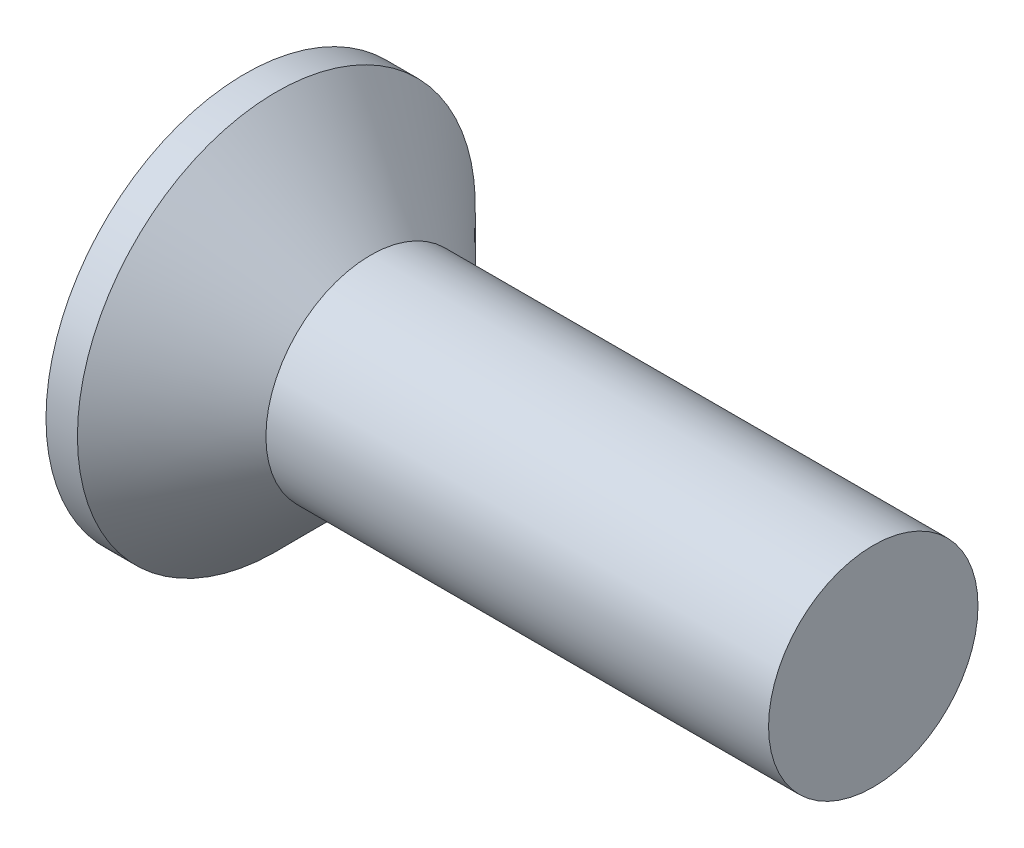
SolidWorks part; units mm, degrees
ref_plane "Plan de face" through (0, 0, 0) normal (0, 0, 1) x (1, 0, 0)
ref_plane "Plan de dessus" through (0, 0, 0) normal (0, 1, 0) x (1, 0, 0)
ref_plane "Plan de droite" through (0, 0, 0) normal (1, 0, 0) x (0, 0, -1)
sketch "Esquisse1" plane through (0, 0, 0) normal (0, 0, 1) x (1, 0, 0)
  line L0 (0, 0) -> (6, 0)
  line L1 (6, 0) -> (6, 1)
  line L2 (6, 1) -> (1.2, 1)
  line L4 (0, 1.9) -> (0, 0)
  line L5 (0, 1.9) -> (0.3, 1.9)
  line L6 (0.3, 1.9) -> (1.2, 1)
  dimension "D1" = 6
  dimension "D2" = 1
  dimension "D3" = 1.9
  dimension "D4" = 1.2
  dimension "D5" = 45
revolve "Révolution1" add sketch "Esquisse1" angle 360 about L0
equation "\"D3@Esquisse1\"=3.8/2"
